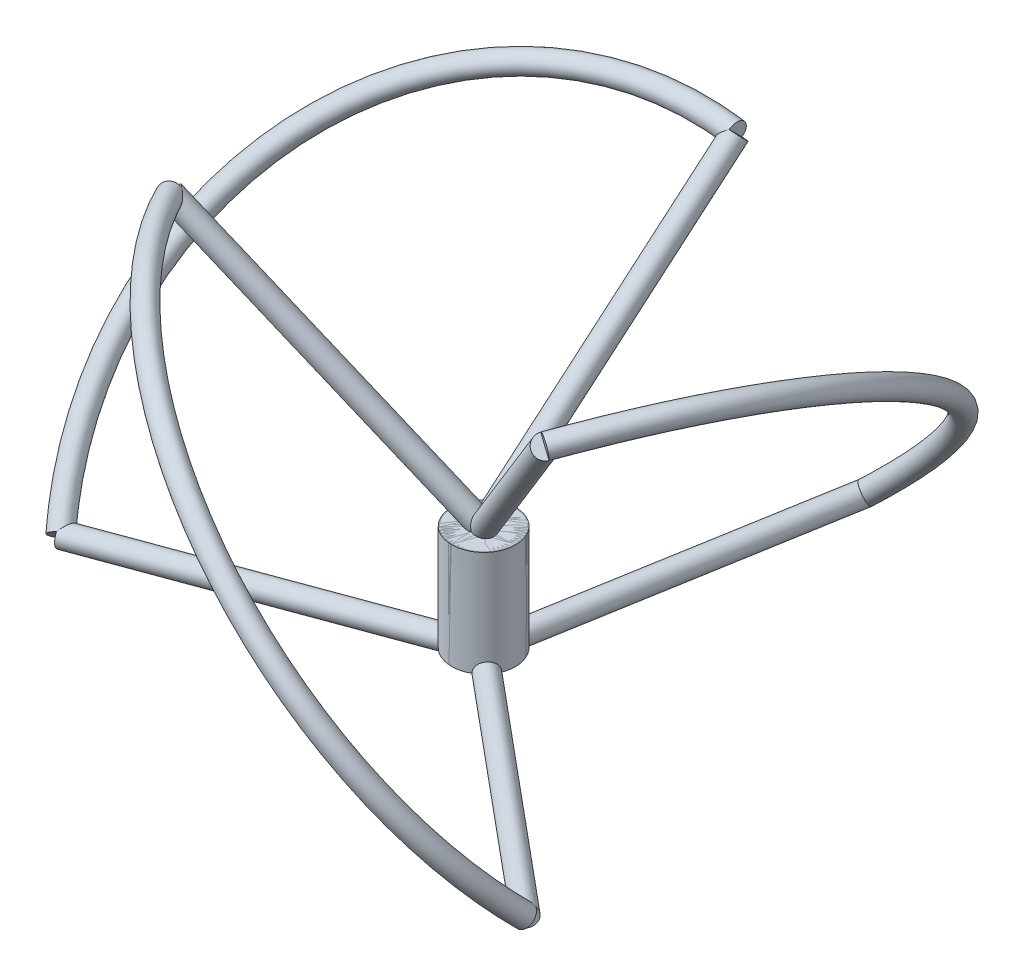
SolidWorks part; units mm, degrees
ref_plane "Front Plane" through (0, 0, 0) normal (0, 0, 1) x (1, 0, 0)
ref_plane "Top Plane" through (0, 0, 0) normal (0, 1, 0) x (1, 0, 0)
ref_plane "Right Plane" through (0, 0, 0) normal (1, 0, 0) x (0, 0, -1)
sketch "Sketch29" plane through (0, 0, 0) normal (0, 1, 0) x (1, 0, 0)
  circle A0 centre (0, 0) radius 3
extrude "Boss-Extrude2" add sketch "Sketch29" along normal blind 10
sketch3d "3DSketch8"
  line L0 (0, 10, 0) -> (5.1655, 10, -30.8201)
  line L1 (0, 10, 0) -> (0, 0, 0) construction
  line L2 (0, 10, 0) -> (24.1082, 10, 19.8835)
  line L3 (0, 10, 0) -> (18.3138, 32.0072, 12.524)
  line L4 (0, 0, 0) -> (5.3131, 0.0071, -30.795)
  line L5 (18.3138, 32.0072, 12.524) -> (5.3131, 0.0071, -30.795)
  arc A0 (5.1655, 10, -30.8201) -> (24.1082, 10, 19.8835) centre (0, 10, 0) cw
  arc A1 (18.3138, 32.0072, 12.524) -> (5.3131, 0.0071, -30.795) centre (1.804, 9.274, -1.1576) cw
  point P6 (0, -21.25, 0)
  point P9 (-19.5276, 30.2291, -10.2355)
  dimension "D4" = 31.25
  dimension "D8" = 31.25
  dimension "D1" = 120
  dimension "D2" = 31.25
  dimension "D3" = 31.25
  dimension "D5" = 45
  dimension "D6" = 31.25
  dimension "D7" = 31.25
sweep "Sweep5" add path "3DSketch8" circular profile diameter 2 parameters "D3"=2
sketch3d "3DSketch9"
  line L0 (0, 10, 0) -> (18.3138, 32.0072, 12.524)
  line L1 (0, 10, 0) -> (0, 0, 0) construction
  line L2 (5.3131, 0.0071, -30.795) -> (0, 0, 0)
  circle A0 centre (18.3138, 32.0072, 12.524) radius 1 construction
  circle A1 centre (5.3131, 0.0071, -30.795) radius 1 construction
  point P6 (18.8187, 32.1526, 11.6732)
  point P11 (4.591, -0.6729, -30.6679)
sweep "Sweep6" add path "3DSketch9" circular profile diameter 2 parameters "D3"=2
sketch3d "3DSketch10"
  line L0 (5.3131, 0.0071, -30.795) -> (0, 0, 0)
  circle A0 centre (5.3131, 0.0071, -30.795) radius 1 construction
  point P4 (4.591, -0.6729, -30.6679)
sweep "Sweep7" add path "3DSketch10" circular profile diameter 2 parameters "D3"=2
pattern_circular "CirPattern3" count 3 over 360 about axis through (-0.0426, 0, -0.0291) along (0, 1, 0) of bodies 113
sketch "Sketch77" plane through (0, 0, 0) normal (1, 0, 0) x (0, 0, -1)
  line L1 (-20.0082, 39.4481) -> (35.1433, 39.4481)
  line L2 (-20.0082, 39.4481) -> (-20.0082, -4.7943)
  line L3 (-20.0082, -4.7943) -> (35.1433, -4.7943)
  line L4 (35.1433, 39.4481) -> (35.1433, -4.7943)
  line L5 (-20.0082, 39.4481) -> (35.1433, -4.7943) construction
  line L6 (-20.0082, -4.7943) -> (35.1433, 39.4481) construction
  point P0 (7.5675, 17.3269)
sketch "Sketch78" plane through (0, 0, 0) normal (1, 0, 0) x (0, 0, -1)
  line L0 (-20.0082, 39.4481) -> (-20.0082, -4.7943) construction
  line L1 (-20.0082, 17.3269) -> (35.1433, 17.3269)
  line L2 (-20.0082, 17.3269) -> (-20.0082, -4.7943)
  line L3 (-20.0082, -4.7943) -> (35.1433, -4.7943)
  line L4 (35.1433, 17.3269) -> (35.1433, -4.7943)
sketch3d "3DSketch12"
  line L0 (1.7453, 32.7094, -21.4971) -> (-29.1219, 0.7194, 11.3742)
  line L1 (1.7453, 32.7094, -21.4971) -> (-0.0387, 10, -0.0806)
  line L3 (-0.0387, 10, -0.0806) -> (-0.0387, 0, -0.0806) construction
  line L4 (-29.1219, 0.7194, 11.3742) -> (0, 0, 0)
